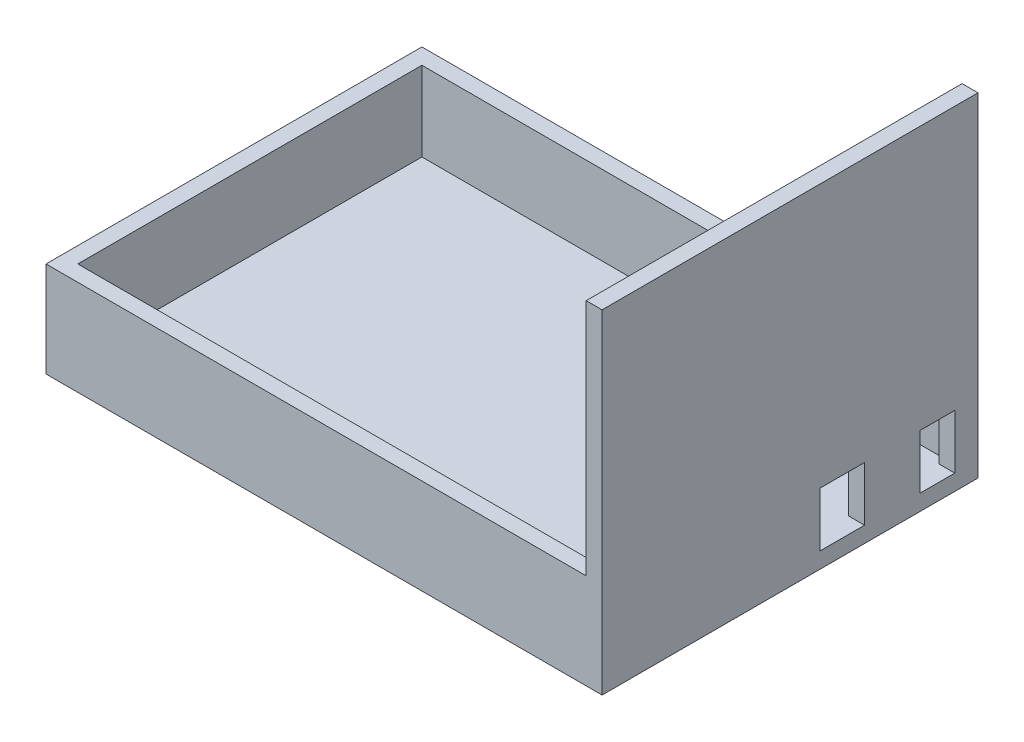
SolidWorks part; units mm, degrees
ref_plane "Płaszczyzna przednia" through (0, 0, 0) normal (0, 0, 1) x (1, 0, 0)
ref_plane "Płaszczyzna górna" through (0, 0, 0) normal (0, 1, 0) x (1, 0, 0)
ref_plane "Płaszczyzna prawa" through (0, 0, 0) normal (1, 0, 0) x (0, 0, -1)
sketch "Szkic1" plane through (0, 0, 0) normal (0, 1, 0) x (1, 0, 0)
  line L1 (-87.5, 59.15) -> (87.5, 59.15)
  line L2 (-87.5, 59.15) -> (-87.5, -59.15)
  line L3 (-87.5, -59.15) -> (87.5, -59.15)
  line L4 (87.5, 59.15) -> (87.5, -59.15)
  line L5 (-87.5, 59.15) -> (87.5, -59.15) construction
  line L6 (-87.5, -59.15) -> (87.5, 59.15) construction
  point P0 (0, 0)
  dimension "D1" = 175
  dimension "D2" = 118.3
extrude "Dodanie-wyciągnięcie1" add sketch "Szkic1" along normal blind 5
sketch "Szkic2" plane through (0, 5, 0) normal (0, 1, 0) x (1, 0, 0)
  line L0 (-87.5, -59.15) -> (87.5, -59.15) construction
  line L1 (-87.5, 59.15) -> (-82.5, 59.15)
  line L2 (-87.5, 59.15) -> (-87.5, -59.15)
  line L3 (-87.5, -59.15) -> (-82.5, -59.15)
  line L4 (-82.5, 59.15) -> (-82.5, -59.15)
  dimension "D1" = 5
extrude "Dodanie-wyciągnięcie2" add sketch "Szkic2" along normal blind 25
sketch "Szkic3" plane through (0, 5, 0) normal (0, 1, 0) x (1, 0, 0)
  line L0 (-82.5, -59.15) -> (87.5, -59.15) construction
  line L1 (87.5, 59.15) -> (82.5, 59.15)
  line L2 (87.5, 59.15) -> (87.5, -59.15)
  line L3 (87.5, -59.15) -> (82.5, -59.15)
  line L4 (82.5, 59.15) -> (82.5, -59.15)
  dimension "D1" = 5
extrude "Dodanie-wyciągnięcie3" add sketch "Szkic3" along normal blind 100
sketch "Szkic4" plane through (0, 5, 0) normal (0, 1, 0) x (1, 0, 0)
  line L0 (82.5, 59.15) -> (82.5, -59.15) construction
  line L1 (-82.5, -59.15) -> (82.5, -59.15)
  line L2 (-82.5, -59.15) -> (-82.5, -54.15)
  line L3 (-82.5, -54.15) -> (82.5, -54.15)
  line L4 (82.5, -59.15) -> (82.5, -54.15)
  dimension "D1" = 5
extrude "Dodanie-wyciągnięcie4" add sketch "Szkic4" along normal blind 25
sketch "Szkic5" plane through (0, 5, 0) normal (0, 1, 0) x (1, 0, 0)
  line L0 (82.5, 59.15) -> (82.5, -54.15) construction
  line L1 (-82.5, 59.15) -> (82.5, 59.15)
  line L2 (-82.5, 59.15) -> (-82.5, 54.15)
  line L3 (-82.5, 54.15) -> (82.5, 54.15)
  line L4 (82.5, 59.15) -> (82.5, 54.15)
  dimension "D1" = 5
extrude "Dodanie-wyciągnięcie5" add sketch "Szkic5" along normal blind 25
sketch "Szkic7" plane through (87.5, 0, 0) normal (1, 0, 0) x (0, 0, -1)
  line L1 (23.45, 22.1) -> (9.45, 22.1)
  line L2 (23.45, 22.1) -> (23.45, 5)
  line L3 (23.45, 5) -> (9.45, 5)
  line L4 (9.45, 22.1) -> (9.45, 5)
  line L7 (10.95, 17.1) -> (21.95, 17.1) construction
  line L8 (22.45, 16.6) -> (22.45, 7.1) construction
  line L9 (10.45, 7.1) -> (10.45, 16.6) construction
  line L10 (54.15, 5) -> (-54.15, 5) construction
  dimension "D1" = 5
  dimension "D2" = 0
  dimension "D3" = 1
  dimension "D4" = 1
extrude "Wytnij-wyciągnięcie1" cut sketch "Szkic7" against normal up to next
sketch "Szkic8" plane through (87.5, 0, 0) normal (1, 0, 0) x (0, 0, -1)
  line L0 (54.15, 5) -> (23.45, 5) construction
  line L1 (40.95, 22.1) -> (51.85, 22.1)
  line L2 (40.95, 22.1) -> (40.95, 5)
  line L3 (40.95, 5) -> (51.85, 5)
  line L4 (51.85, 22.1) -> (51.85, 5)
  line L5 (41.95, 7) -> (41.95, 17.1) construction
  line L6 (50.85, 17.1) -> (50.85, 7) construction
  line L7 (41.95, 17.1) -> (50.85, 17.1) construction
  dimension "D1" = 0
  dimension "D2" = 1
  dimension "D3" = 1
  dimension "D4" = 5
extrude "Wytnij-wyciągnięcie2" cut sketch "Szkic8" against normal up to next
